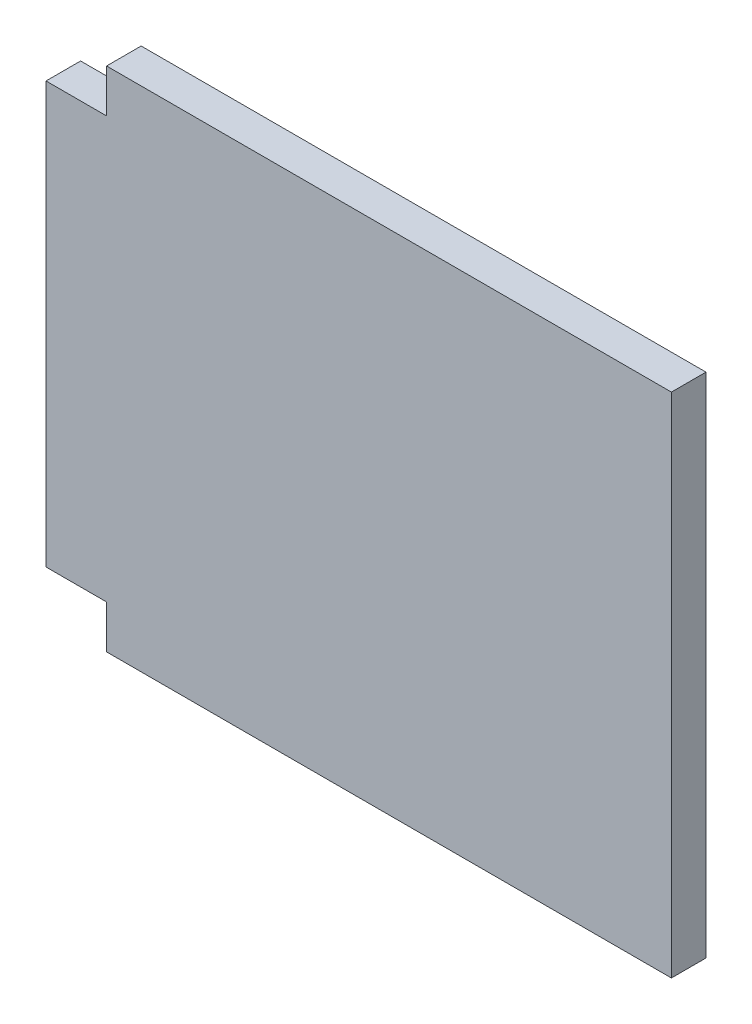
SolidWorks part; units mm, degrees
ref_plane "Plan de face" through (0, 0, 0) normal (0, 0, 1) x (1, 0, 0)
ref_plane "Plan de dessus" through (0, 0, 0) normal (0, 1, 0) x (1, 0, 0)
ref_plane "Plan de droite" through (0, 0, 0) normal (1, 0, 0) x (0, 0, -1)
sketch "Esquisse1" plane through (0, 0, 0) normal (0, 0, 1) x (1, 0, 0)
  line L0 (-48.0516, 5.41) -> (-51.5516, 5.41)
  line L1 (-48.0516, 32.25) -> (-15.3916, 32.25)
  line L2 (-48.0516, 32.25) -> (-48.0516, 2.91)
  line L3 (-48.0516, 2.91) -> (-15.3916, 2.91)
  line L4 (-15.3916, 32.25) -> (-15.3916, 2.91)
  line L5 (-51.5516, 5.41) -> (-51.5516, 29.75)
  line L6 (-51.5516, 29.75) -> (-48.0516, 29.75)
  point P6 (-49.8016, 29.75)
  point P9 (-51.5516, 17.58)
  point P10 (-48.0516, 17.58)
  dimension "D1" = 32.66
  dimension "D2" = 29.34
  dimension "D3" = 36.16
  dimension "D4" = 24.34
  dimension "D5" = 0
extrude "Boss.-Extru.1" add sketch "Esquisse1" along normal blind 2 contours L4 L1 L2 L3 | L6 L5 L0 L2
